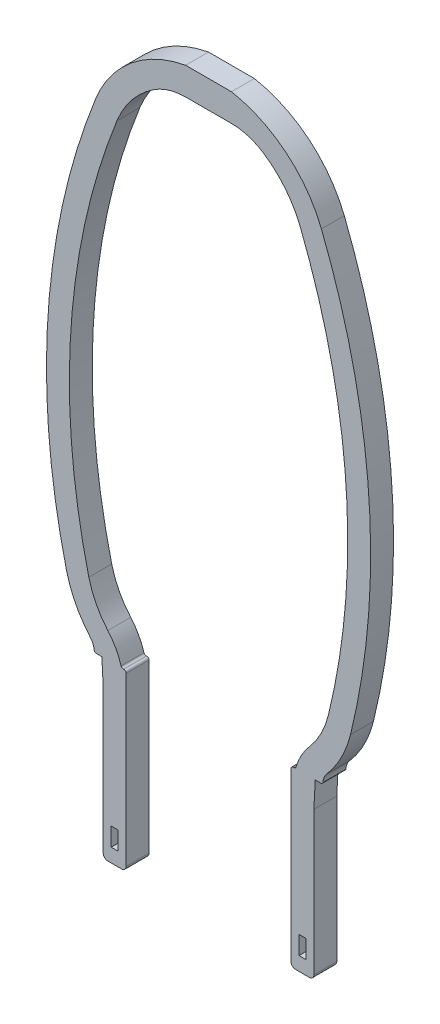
SolidWorks part; units mm, degrees
ref_plane "Front Plane" through (0, 0, 0) normal (0, 0, 1) x (1, 0, 0)
ref_plane "Top Plane" through (0, 0, 0) normal (0, 1, 0) x (1, 0, 0)
ref_plane "Right Plane" through (0, 0, 0) normal (1, 0, 0) x (0, 0, -1)
sketch "Sketch1" plane through (0, 0, 0) normal (0, 0, 1) x (1, 0, 0)
  line L0 (0, 0) -> (0, 115) construction
  line L1 (-18, -38) -> (-18, 0) construction
  line L2 (-23, 0) -> (-23, -38)
  line L3 (0, 0) -> (-23, 0) construction
  line L4 (0, 115) -> (-57.1655, 115) construction
  line L5 (-18, 0) -> (-30.8199, 22.2047) construction
  line L6 (-22.3301, -2.5) -> (-23, -38) construction
  line L7 (-23, -38) -> (-18, -38)
  line L8 (-18, -38) -> (-18, 0)
  line L9 (-5, 115) -> (0, 115)
  line L12 (23, -38) -> (18, -38)
  line L13 (18, -38) -> (18, 0)
  line L14 (5, 115) -> (0, 115)
  line L19 (-5, 121) -> (5, 121)
  line L20 (-5, 121) -> (-5, 115) construction
  line L21 (-25, 0) -> (-23, 0)
  line L22 (5, 121) -> (5, 115) construction
  line L23 (21.25, -6) -> (19.75, -6) construction
  line L24 (-21.25, -31) -> (-19.75, -31) construction
  line L25 (-21.25, -31) -> (-21.25, -35) construction
  line L26 (-21.25, -35) -> (-19.75, -35) construction
  line L27 (-19.75, -31) -> (-19.75, -35) construction
  line L28 (19.75, -31) -> (21.25, -31) construction
  line L29 (19.75, -31) -> (19.75, -35) construction
  line L30 (19.75, -35) -> (21.25, -35) construction
  line L31 (21.25, -31) -> (21.25, -35) construction
  line L32 (-21.25, -6) -> (-19.75, -6) construction
  line L33 (-21.25, -6) -> (-21.25, -10) construction
  line L34 (-21.25, -10) -> (-19.75, -10) construction
  line L35 (-19.75, -6) -> (-19.75, -10) construction
  line L36 (21.25, -6) -> (21.25, -10) construction
  line L37 (21.25, -10) -> (19.75, -10) construction
  line L38 (19.75, -6) -> (19.75, -10) construction
  line L39 (-19.75, -31) -> (-19.75, -35)
  line L40 (-21.25, -35) -> (-19.75, -35)
  line L41 (-21.25, -31) -> (-21.25, -35)
  line L42 (-21.25, -31) -> (-19.75, -31)
  line L43 (21.25, -31) -> (21.25, -35)
  line L44 (19.75, -35) -> (21.25, -35)
  line L45 (19.75, -31) -> (19.75, -35)
  line L46 (19.75, -31) -> (21.25, -31)
  line L47 (18, 0) -> (19, 0)
  line L48 (-18, 0) -> (-19, 0)
  line L49 (23, 0) -> (23, -38)
  line L50 (25, 0) -> (23, 0)
  arc A0 (-18, 0) -> (-22, 5.6069) centre (-49.0905, -17.9501) ccw construction
  arc A1 (-22, 5.6069) -> (-26.1477, 13.6069) centre (-7.545, 18.1764) cw
  arc A2 (-12, 112.8885) -> (-5, 115) centre (-5, 102.3412) cw
  arc A3 (-26.1477, 13.6069) -> (-20, 103.0261) centre (116.7351, 48.7045) cw
  arc A4 (-20, 103.0261) -> (-12, 112.8885) centre (-0.2463, 95.1784) cw
  arc A5 (-22.3301, -2.5) -> (-25.773, 2.326) centre (-49.0905, -17.9501) ccw construction
  arc A6 (-25.773, 2.326) -> (-31.0033, 12.4141) centre (-7.545, 18.1764) cw
  arc A7 (-31.0033, 12.4141) -> (-24.6467, 104.8722) centre (116.7351, 48.7045) cw
  arc A8 (-24.6467, 104.8722) -> (-14.7649, 117.0545) centre (-0.2463, 95.1784) cw
  arc A9 (-14.7649, 117.0545) -> (-5, 120) centre (-5, 102.3412) cw construction
  arc A10 (14.7649, 117.0545) -> (5, 120) centre (5, 102.3412) ccw construction
  arc A11 (24.6467, 104.8722) -> (14.7649, 117.0545) centre (0.2463, 95.1784) ccw
  arc A12 (31.0033, 12.4141) -> (24.6467, 104.8722) centre (-116.7351, 48.7045) ccw
  arc A13 (25.773, 2.326) -> (31.0033, 12.4141) centre (7.545, 18.1764) ccw
  arc A15 (18, 0) -> (22, 5.6069) centre (49.0905, -17.9501) cw construction
  arc A16 (22, 5.6069) -> (26.1477, 13.6069) centre (7.545, 18.1764) ccw
  arc A17 (26.1477, 13.6069) -> (20, 103.0261) centre (-116.7351, 48.7045) ccw
  arc A18 (20, 103.0261) -> (12, 112.8885) centre (0.2463, 95.1784) ccw
  arc A19 (12, 112.8885) -> (5, 115) centre (5, 102.3412) ccw
  arc A20 (-14.7649, 117.0545) -> (-5, 120) centre (-5, 102.3412) cw construction
  arc A23 (14.7649, 117.0545) -> (5, 121) centre (0.2463, 95.1784) ccw
  arc A25 (-14.7649, 117.0545) -> (-5, 121) centre (-0.2463, 95.1784) cw
  arc A26 (-25.773, 2.326) -> (-25, 0) centre (-28.177, 0.2356) cw
  arc A27 (22, 5.6069) -> (19, 0) centre (32.7801, -3.7672) ccw
  arc A28 (-22, 5.6069) -> (-19, 0) centre (-32.7801, -3.7672) cw
  arc A29 (25.773, 2.326) -> (25, 0) centre (28.177, 0.2356) ccw
  dimension "D13" = 5
  dimension "D11" = 1
  dimension "D1" = 18
  dimension "D2" = 115
  dimension "D3" = 5
  dimension "D4" = 31
  dimension "D5" = 60
  dimension "D6" = 5
  dimension "D7" = 12
  dimension "D8" = 8
  dimension "D9" = 8
  dimension "D10" = 22
  dimension "D12" = 3
  dimension "D15" = 2
  dimension "D16" = 6
  dimension "D17" = 4
  dimension "D18" = 1.5
  dimension "D19" = 1.75
  dimension "D21" = 6
  dimension "D22" = 2
extrude "Boss-Extrude2" add sketch "Sketch1" along normal blind 5
fillet "Fillet1" radius 0.5 6 edges at (-18, 0, 2.5) (18, 0, 2.5) (19, 0, 2.5) (-19, 0, 2.5) (-25, 0, 2.5) (25, 0, 2.5)
chamfer "Chamfer1" distance 0.3 angle 87 2 edges at (23, 0, 2.5) (-23, 0, 2.5)
fillet "Fillet2" radius 1 4 edges at (-23, -38, 2.5) (-18, -38, 2.5) (23, -38, 2.5) (18, -38, 2.5)
